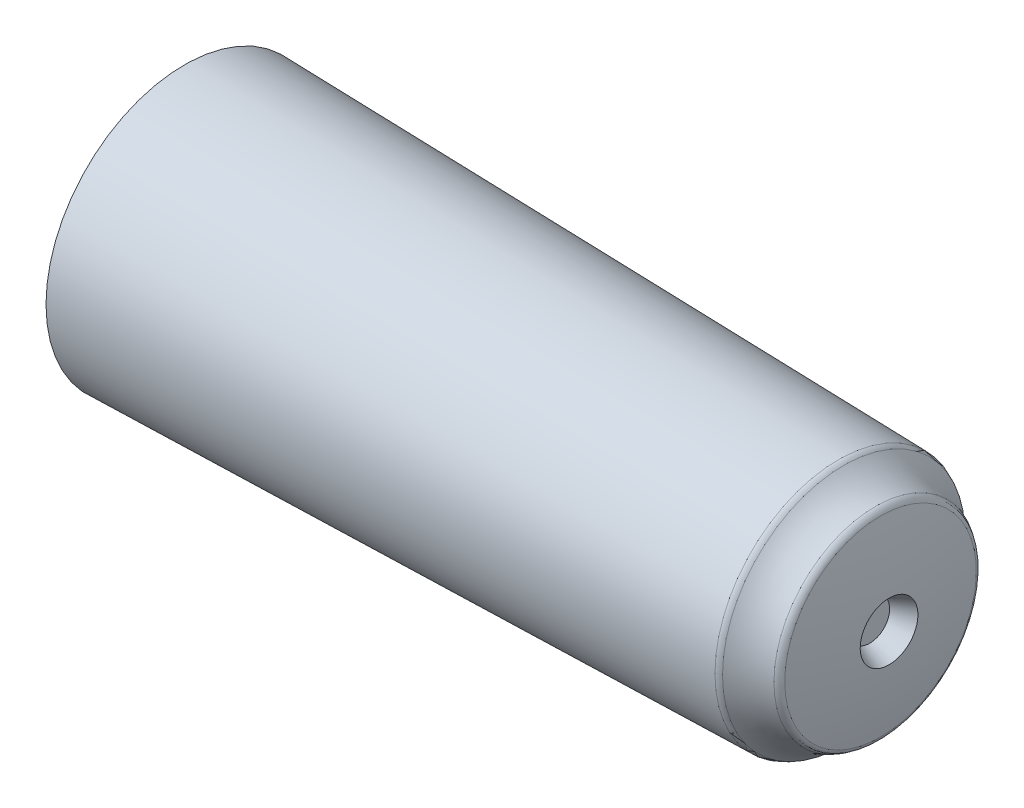
SolidWorks part; units mm, degrees
ref_plane "Plano frontal" through (0, 0, 0) normal (0, 0, 1) x (1, 0, 0)
ref_plane "Plano superior" through (0, 0, 0) normal (0, 1, 0) x (1, 0, 0)
ref_plane "Plano direito" through (0, 0, 0) normal (1, 0, 0) x (0, 0, -1)
sketch "Esboço1" plane through (0, 0, 0) normal (0, 0, 1) x (1, 0, 0)
  line L0 (64.7214, 0) -> (65.7217, 0)
  line L1 (59.4986, 2.8989) -> (65.2949, 2.8989) construction
  line L2 (65.2605, 3.1096) -> (65.2949, 2.8989)
  line L3 (65.2949, 2.8989) -> (65.4396, 1.7477)
  line L31 (7.0434, 5.2649) -> (7.0434, 6.1438) construction
  line L32 (6.7434, 4.9773) -> (6.7434, 5.2649) construction
  line L33 (6.7434, 5.2649) -> (7.0434, 5.2649) construction
  line L34 (6.7434, 4.9773) -> (6.7227, 4.8999) construction
  line L35 (6.7227, 4.8999) -> (5.9727, 4.8999) construction
  line L36 (5.9202, 5.0958) -> (5.9727, 4.8999) construction
  line L37 (5.3718, 5.1699) -> (5.8236, 5.1699) construction
  line L38 (5.2752, 5.0958) -> (5.2227, 4.8999) construction
  line L39 (5.2227, 4.8999) -> (4.4727, 4.8999) construction
  line L40 (4.4202, 5.0958) -> (4.4727, 4.8999) construction
  line L41 (3.8718, 5.1699) -> (4.3236, 5.1699) construction
  line L42 (3.7752, 5.0958) -> (3.7227, 4.8999) construction
  line L43 (3.7227, 4.8999) -> (2.9727, 4.8999) construction
  line L44 (2.9202, 5.0958) -> (2.9727, 4.8999) construction
  line L45 (2.3718, 5.1699) -> (2.8236, 5.1699) construction
  line L46 (2.2752, 5.0958) -> (2.2227, 4.8999) construction
  line L47 (2.2227, 4.8999) -> (1.4727, 4.8999) construction
  line L48 (1.4202, 5.0958) -> (1.4727, 4.8999) construction
  line L49 (0.8718, 5.1699) -> (1.3236, 5.1699) construction
  line L50 (0.7752, 5.0958) -> (0.7227, 4.8999) construction
  line L51 (0.7227, 4.8999) -> (0.5284, 4.8999) construction
  line L52 (0.5284, 3.976) -> (0.5284, 4.8999) construction
  line L53 (0.5284, 3.976) -> (42.4168, 3.75) construction
  line L54 (49.3163, 3.332) -> (42.4168, 3.75) construction
  line L55 (49.3163, 2.815) -> (49.3163, 3.332) construction
  line L56 (50.6219, 2.815) -> (49.3163, 2.815) construction
  line L57 (50.6219, 2.7819) -> (50.6219, 3.4085) construction
  line L58 (39.1725, 4.6704) -> (39.9897, 4.6704) construction
  line L59 (38.9647, 4.7904) -> (39.1725, 4.6704) construction
  line L60 (38.4647, 4.7904) -> (38.9647, 4.7904) construction
  line L61 (38.4647, 4.7904) -> (38.4647, 5.5359) construction
  line L76 (38.4647, 4.8404) -> (39.2893, 4.8404)
  line L77 (65.1319, 3.3087) -> (64.1488, 3.9683)
  line L78 (65.3966, 1.7029) -> (59.9988, 1.75) construction
  line L79 (59.9988, 1.75) -> (59.9988, 2.3986) construction
  line L80 (59.9988, 2.3986) -> (59.9988, 1.75) construction
  line L81 (59.9988, 2.3986) -> (59.4986, 2.8989) construction
  line L82 (59.4986, 2.8989) -> (53.3343, 2.9527) construction
  line L83 (53.3343, 2.9527) -> (53.0554, 3.2315) construction
  line L84 (53.0554, 3.2315) -> (50.9337, 3.2501) construction
  line L85 (50.9337, 2.9552) -> (50.9337, 3.2501) construction
  line L86 (52.9186, 2.7655) -> (51.5712, 2.7773) construction
  line L87 (59.1988, 2.3043) -> (53.9417, 2.3502) construction
  line L88 (59.1988, 1.1479) -> (59.1988, 2.3043) construction
  line L89 (54.1379, 2.9457) -> (52.8032, 4.2804) construction
  line L93 (65.7217, 0.7905) -> (66.4881, 1.1479)
  line L95 (65.7217, 0) -> (65.7217, 0.7905)
  line L96 (0, 0) -> (119.6441, 0) construction
  line L97 (38.4647, 5.5059) -> (38.4647, 4.8404)
  line L98 (59.1988, 1.1479) -> (65.0036, 1.1479) construction
  arc A0 (65.0036, 1.1479) -> (65.4396, 1.7477) centre (67.7907, -0.4198) cw
  arc A12 (38.4647, 5.5359) -> (7.0434, 6.1438) centre (-138.0398, -8304.8403) ccw construction
  arc A13 (5.9202, 5.0958) -> (5.8236, 5.1699) centre (5.8236, 5.0699) ccw construction
  arc A14 (5.3718, 5.1699) -> (5.2752, 5.0958) centre (5.3718, 5.0699) ccw construction
  arc A15 (4.4202, 5.0958) -> (4.3236, 5.1699) centre (4.3236, 5.0699) ccw construction
  arc A16 (3.8718, 5.1699) -> (3.7752, 5.0958) centre (3.8718, 5.0699) ccw construction
  arc A17 (2.9202, 5.0958) -> (2.8236, 5.1699) centre (2.8236, 5.0699) ccw construction
  arc A18 (2.3718, 5.1699) -> (2.2752, 5.0958) centre (2.3718, 5.0699) ccw construction
  arc A19 (1.4202, 5.0958) -> (1.3236, 5.1699) centre (1.3236, 5.0699) ccw construction
  arc A20 (0.8718, 5.1699) -> (0.7752, 5.0958) centre (0.8718, 5.0699) ccw construction
  arc A21 (50.6219, 3.4085) -> (50.3282, 3.597) centre (50.2219, 3.1085) ccw construction
  arc A22 (50.3282, 3.597) -> (40.9396, 4.6704) centre (40.304, -42.4866) ccw construction
  arc A23 (40.9396, 4.6704) -> (39.9897, 4.6704) centre (40.4647, 3.7904) ccw construction
  arc A29 (65.0036, 1.1479) -> (64.7214, 0) centre (67.2214, -0.0059) ccw
  arc A41 (64.4769, 4.9127) -> (38.4647, 5.5059) centre (-138.0398, -8304.8403) ccw
  arc A42 (64.6855, 4.821) -> (64.4769, 4.9127) centre (64.4695, 4.6128) ccw
  arc A43 (64.6855, 4.821) -> (65.946, 4.0365) centre (66.872, 6.9292) ccw
  arc A44 (66.1488, 3.8089) -> (65.946, 4.0365) centre (65.8545, 3.7508) ccw
  arc A45 (66.4881, 1.1479) -> (66.1488, 3.8089) centre (46.8792, 0) ccw
  arc A50 (39.2893, 4.8404) -> (40.471, 4.8429) centre (39.8772, 6.2204) ccw
  arc A51 (40.471, 4.8429) -> (63.9855, 4.0191) centre (70.7629, 533.5044) ccw
  arc A52 (64.1488, 3.9683) -> (63.9855, 4.0191) centre (63.9817, 3.7192) ccw
  arc A53 (65.2605, 3.1096) -> (65.1319, 3.3087) centre (64.9647, 3.0595) ccw
  arc A54 (65.4396, 1.7477) -> (65.2605, 3.1096) centre (46.8792, 0) ccw construction
  arc A55 (65.4396, 1.7477) -> (65.3966, 1.7029) centre (67.2214, -0.0059) ccw construction
  arc A56 (50.9337, 2.9552) -> (51.5712, 2.7773) centre (51.3532, 3.2273) ccw construction
  arc A57 (52.9186, 2.7655) -> (53.9417, 2.3502) centre (53.9548, 3.8501) ccw construction
revolve "Revolução1" add sketch "Esboço1" angle 360 about L96
sketch "Esboço2" plane through (0, 0, 0) normal (0, 0, 1) x (1, 0, 0)
  line L0 (65.1319, 3.3087) -> (64.1488, 3.9683) construction
  line L1 (65.1319, 3.3087) -> (64.1488, 3.9683)
  line L2 (65.2605, 3.1096) -> (65.2949, 2.8989) construction
  line L3 (65.2949, 2.8989) -> (65.4396, 1.7477) construction
  line L4 (65.2605, 3.1096) -> (65.2949, 2.8989)
  line L5 (65.2949, 2.8989) -> (65.4396, 1.7477)
  line L6 (65.4396, 1.7477) -> (60.1396, 1.8145)
  line L7 (60.1396, 1.8145) -> (60.1396, 2.8145)
  line L8 (60.1396, 2.8145) -> (54.1883, 2.8145)
  line L9 (53.7895, 3.0129) -> (52.8319, 4.2795)
  arc A0 (40.471, 4.8429) -> (63.9855, 4.0191) centre (70.7629, 533.5044) ccw construction
  arc A1 (40.471, 4.8429) -> (63.9855, 4.0191) centre (70.7629, 533.5044) ccw
  arc A2 (64.1488, 3.9683) -> (63.9855, 4.0191) centre (63.9817, 3.7192) ccw construction
  arc A3 (64.1488, 3.9683) -> (63.9855, 4.0191) centre (63.9817, 3.7192) ccw
  arc A4 (65.2605, 3.1096) -> (65.1319, 3.3087) centre (64.9647, 3.0595) ccw construction
  arc A5 (65.4396, 1.7477) -> (65.2605, 3.1096) centre (46.8792, 0) ccw construction
  arc A6 (65.2605, 3.1096) -> (65.1319, 3.3087) centre (64.9647, 3.0595) ccw
  arc A7 (65.4396, 1.7477) -> (65.2605, 3.1096) centre (46.8792, 0) ccw
  arc A8 (54.1883, 2.8145) -> (53.7895, 3.0129) centre (54.1883, 3.3145) cw
  point P3 (52.8319, 4.2795)
  point P18 (53.9396, 2.8145)
  dimension "D4" = 0.5
  dimension "D1" = 5.3
  dimension "D2" = 11.5
  dimension "D3" = 1
extrude "Ressalto-extrusão1" add sketch "Esboço2" along normal mid plane 0.6 contours L4 A6 L1 A3 A1 L9 L8 L7 L6 L5
pattern_circular "PadrãoCircular1" count 4 over 360 about axis through (0, 0, 0) along (1, 0, 0) of "Ressalto-extrusão1"
